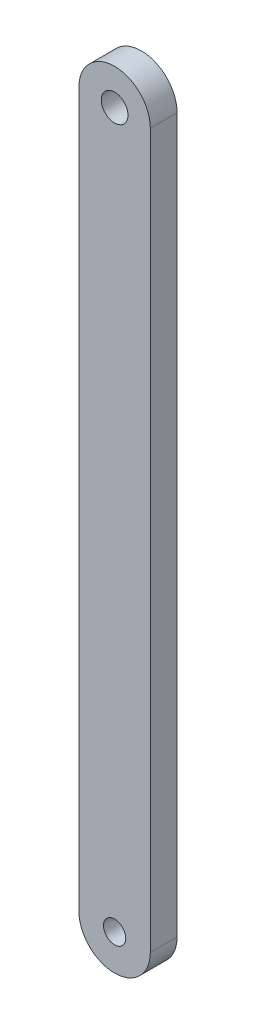
SolidWorks part; units mm, degrees
ref_plane "前基準面" through (0, 0, 0) normal (0, 0, 1) x (1, 0, 0)
ref_plane "上基準面" through (0, 0, 0) normal (0, 1, 0) x (1, 0, 0)
ref_plane "右基準面" through (0, 0, 0) normal (1, 0, 0) x (0, 0, -1)
sketch "草圖1" plane through (0, 0, 0) normal (0, 0, 1) x (1, 0, 0)
  line L0 (24.3003, 85.0002) -> (24.3003, 5)
  line L1 (32.3001, 5) -> (32.3001, 85.0001)
  arc A0 (24.3003, 85.0002) -> (32.3001, 85.0001) centre (28.3002, 85.0002) cw
  arc A1 (32.3001, 85.0001) -> (24.3003, 85.0002) centre (28.3002, 85.0002) ccw construction
  arc A2 (24.3003, 5.0001) -> (32.3001, 5.0001) centre (28.3002, 5) ccw construction
  arc A3 (24.3003, 5) -> (32.3001, 5) centre (28.3002, 5) ccw
  circle A4 centre (28.3002, 5) radius 1.25
  circle A5 centre (28.3003, 5.0001) radius 1.25 construction
  circle A6 centre (28.3002, 85.0002) radius 1.5
  circle A7 centre (28.3003, 85.0001) radius 1.5 construction
extrude "填料-伸長1" add sketch "草圖1" along normal blind 3
